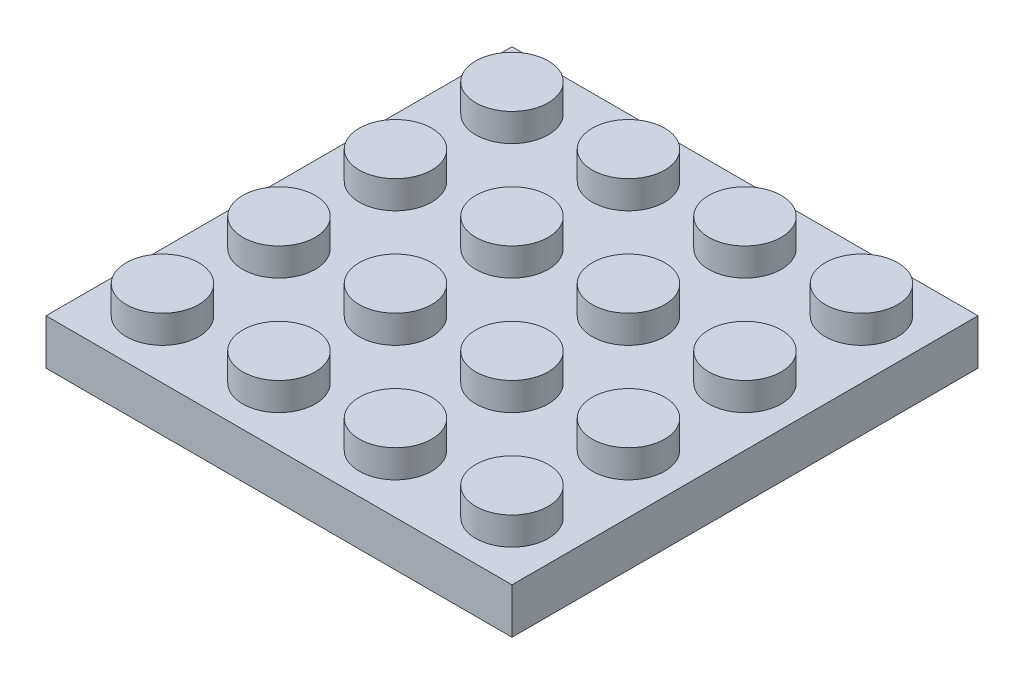
SolidWorks part; units mm, degrees
ref_plane "Front Plane" through (0, 0, 0) normal (0, 0, 1) x (1, 0, 0)
ref_plane "Top Plane" through (0, 0, 0) normal (0, 1, 0) x (1, 0, 0)
ref_plane "Right Plane" through (0, 0, 0) normal (1, 0, 0) x (0, 0, -1)
sketch "Sketch1" plane through (0, 0, 0) normal (0, 1, 0) x (1, 0, 0)
  line L0 (-50.5645, 33.8665) -> (-50.5645, 2.0665)
  line L1 (-50.5645, 2.0665) -> (-18.7645, 2.0665)
  line L2 (-18.7645, 2.0665) -> (-18.7645, 33.8665)
  line L3 (-18.7645, 33.8665) -> (-50.5645, 33.8665)
  dimension "D1" = 31.8
  dimension "D2" = 31.8
extrude "Boss-Extrude1" add sketch "Sketch1" along normal blind 3.1
sketch "Sketch2" plane through (0, 0, 0) normal (0, -1, 0) x (1, 0, 0)
  line L0 (-49.0645, -3.5665) -> (-20.2645, -3.5665)
  line L1 (-20.2645, -3.5665) -> (-20.2645, -32.3665)
  line L2 (-20.2645, -32.3665) -> (-49.0645, -32.3665)
  line L3 (-49.0645, -32.3665) -> (-49.0645, -3.5665)
  line L4 (-50.5645, -33.8665) -> (-50.5645, -2.0665) construction
  line L5 (-50.5645, -2.0665) -> (-18.7645, -2.0665) construction
  line L6 (-18.7645, -2.0665) -> (-18.7645, -33.8665) construction
  line L7 (-18.7645, -33.8665) -> (-50.5645, -33.8665) construction
  dimension "D1" = 1.5
  dimension "D2" = 1.5
  dimension "D3" = 1.5
  dimension "D4" = 1.5
extrude "Cut-Extrude1" cut sketch "Sketch2" against normal blind 1.9
sketch "Sketch3" plane through (0, 3.1, 0) normal (0, 1, 0) x (1, 0, 0)
  line L0 (-50.5645, 33.8665) -> (-50.5645, 2.0665) construction
  line L1 (-18.7645, 33.8665) -> (-50.5645, 33.8665) construction
  line L2 (-50.5645, 2.0665) -> (-18.7645, 2.0665) construction
  line L3 (-18.7645, 2.0665) -> (-18.7645, 33.8665) construction
  circle A0 centre (-46.5895, 29.8915) radius 2.475
  circle A1 centre (-30.6895, 29.8915) radius 2.475
  circle A2 centre (-38.6395, 29.8915) radius 2.475
  circle A3 centre (-22.7395, 29.8915) radius 2.475
  circle A4 centre (-46.5895, 21.9415) radius 2.475
  circle A5 centre (-38.6395, 21.9415) radius 2.475
  circle A6 centre (-30.6895, 21.9415) radius 2.475
  circle A7 centre (-22.7395, 21.9415) radius 2.475
  circle A8 centre (-22.7395, 13.9915) radius 2.475
  circle A9 centre (-22.7395, 6.0415) radius 2.475
  circle A10 centre (-30.6895, 13.9915) radius 2.475
  circle A11 centre (-30.6895, 6.0415) radius 2.475
  circle A12 centre (-38.6395, 13.9915) radius 2.475
  circle A13 centre (-38.6395, 6.0415) radius 2.475
  circle A14 centre (-46.5895, 13.9915) radius 2.475
  circle A15 centre (-46.5895, 6.0415) radius 2.475
  dimension "D1" = 4.95
  dimension "D2" = 4.95
  dimension "D3" = 4.95
  dimension "D4" = 4.95
  dimension "D5" = 4.95
  dimension "D6" = 4.95
  dimension "D7" = 4.95
  dimension "D8" = 4.95
  dimension "D9" = 4.95
  dimension "D10" = 4.95
  dimension "D11" = 4.95
  dimension "D12" = 4.95
  dimension "D13" = 4.95
  dimension "D14" = 4.95
  dimension "D15" = 4.95
  dimension "D16" = 4.95
  dimension "D33" = 7.95
  dimension "D17" = 3.975
  dimension "D18" = 3.975
  dimension "D19" = 3.975
  dimension "D20" = 3.975
  dimension "D21" = 3.975
  dimension "D22" = 3.975
  dimension "D23" = 3.975
  dimension "D24" = 3.975
  dimension "D25" = 3.975
  dimension "D26" = 3.975
  dimension "D27" = 3.975
  dimension "D28" = 3.975
  dimension "D29" = 3.975
  dimension "D30" = 3.975
  dimension "D31" = 3.975
  dimension "D32" = 3.975
  dimension "D34" = 7.95
  dimension "D35" = 7.95
  dimension "D36" = 7.95
  dimension "D37" = 7.95
  dimension "D38" = 7.95
  dimension "D39" = 7.95
  dimension "D40" = 7.95
  dimension "D41" = 7.95
  dimension "D42" = 7.95
  dimension "D43" = 7.95
  dimension "D44" = 7.95
  dimension "D45" = 7.95
  dimension "D46" = 7.95
  dimension "D47" = 7.95
extrude "Boss-Extrude2" add sketch "Sketch3" along normal blind 1.9
